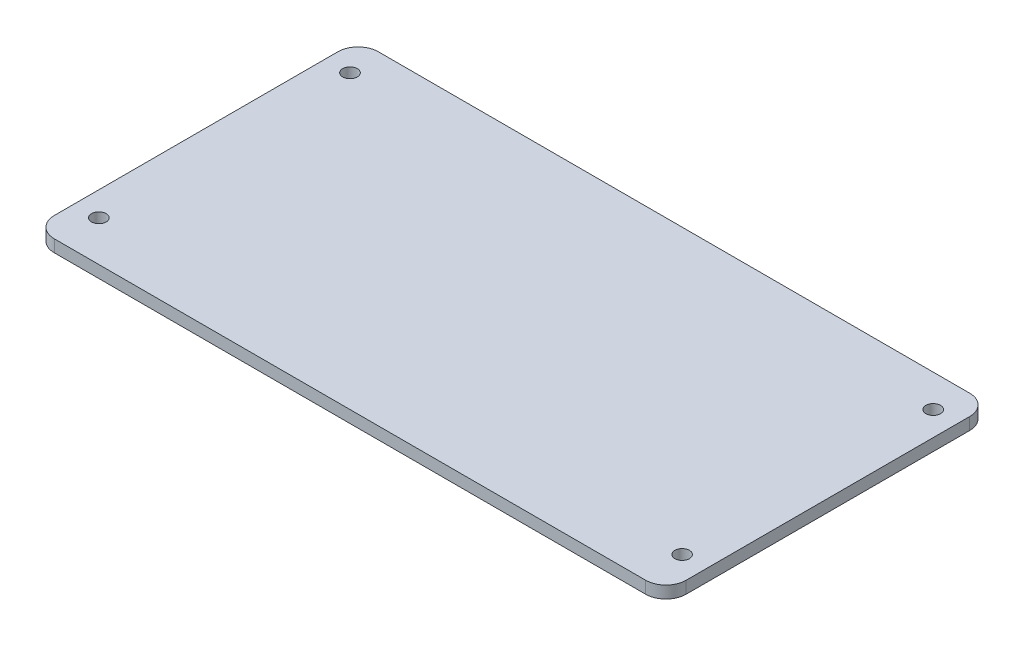
SolidWorks part; units mm, degrees
material "PLA 100% Infill"
ref_plane "Front Plane" through (0, 0, 0) normal (0, 0, 1) x (1, 0, 0)
ref_plane "Top Plane" through (0, 0, 0) normal (0, 1, 0) x (1, 0, 0)
ref_plane "Right Plane" through (0, 0, 0) normal (1, 0, 0) x (0, 0, -1)
sketch "Sketch1" plane through (0, 0, 0) normal (0, 1, 0) x (1, 0, 0)
  line L1 (0, 0) -> (-156, 0)
  line L2 (0, 0) -> (0, -80)
  line L3 (0, -80) -> (-156, -80)
  line L4 (-156, 0) -> (-156, -80)
  circle A0 centre (-150, -70) radius 1.8
  circle A1 centre (-6, -70) radius 1.8
  circle A2 centre (-6, -8) radius 1.8
  circle A3 centre (-150, -8) radius 1.8
  point P9 (0, -71.4504)
  dimension "D3" = 3.6
  dimension "D8" = 62
  dimension "D9" = 6
  dimension "D4" = 10
  dimension "D1" = 156
  dimension "D2" = 80
  dimension "D5" = 6
  dimension "D6" = 2
  dimension "D7" = 2
extrude "Boss-Extrude1" add sketch "Sketch1" along normal blind 3
fillet "Fillet1" radius 5 4 edges at (-156, 1.5, 0) (0, 1.5, 0) (0, 1.5, 80) (-156, 1.5, 80)
